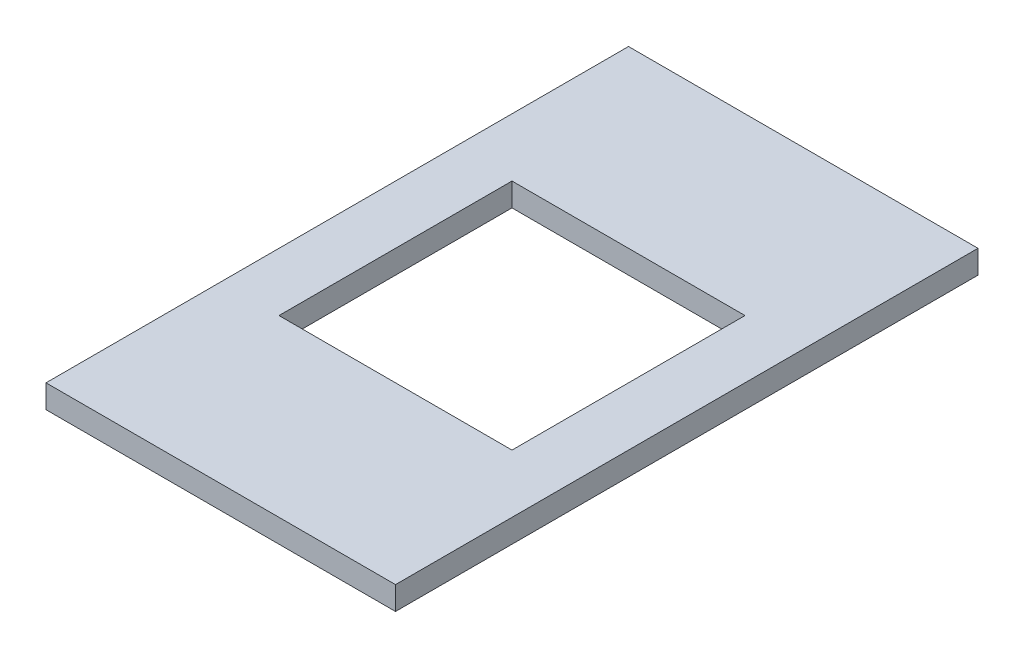
SolidWorks part; units mm, degrees
ref_plane "Front Plane" through (0, 0, 0) normal (0, 0, 1) x (1, 0, 0)
ref_plane "Top Plane" through (0, 0, 0) normal (0, 1, 0) x (1, 0, 0)
ref_plane "Right Plane" through (0, 0, 0) normal (1, 0, 0) x (0, 0, -1)
sketch "Sketch1" plane through (0, 0, 0) normal (0, 1, 0) x (1, 0, 0)
  line L1 (0, 0) -> (-150, 0)
  line L2 (0, 0) -> (0, 30)
  line L3 (0, 30) -> (-150, 30)
  line L4 (-150, 0) -> (-150, 30)
  dimension "D1" = 30
  dimension "D2" = 150
extrude "Boss-Extrude1" add sketch "Sketch1" along normal blind 10
sketch "Sketch8" plane through (0, 0, 0) normal (0, -1, 0) x (-1, 0, 0)
  line L0 (150, 0) -> (0, 30)
  line L1 (150, 30) -> (0, 0)
  line L2 (150, 0) -> (0, 0) construction
sketch "Sketch9" plane through (0, 0, 0) normal (0, -1, 0) x (1, 0, 0)
  line L0 (-150, -30) -> (0, 0) construction
  line L1 (0, -140) -> (-150, -140)
  line L2 (0, -140) -> (0, 110)
  line L3 (0, 110) -> (-150, 110)
  line L4 (-150, -140) -> (-150, 110)
  line L5 (0, -140) -> (-150, 110) construction
  line L6 (0, 110) -> (-150, -140) construction
  line L8 (-125, -65) -> (-25, -65)
  line L9 (-125, -65) -> (-125, 35)
  line L10 (-125, 35) -> (-25, 35)
  line L11 (-25, -65) -> (-25, 35)
  line L12 (-125, -65) -> (-25, 35) construction
  line L13 (-125, 35) -> (-25, -65) construction
  point P0 (-75, -15)
  point P7 (-75, -15)
  point P12 (-75, 110)
  point P13 (-75, -140)
  dimension "D1" = 250
  dimension "D2" = 150
  dimension "D3" = 100
  dimension "D4" = 100
extrude "Boss-Extrude3" add sketch "Sketch9" along normal blind 10
sketch "Sketch19" plane through (0, -10, 0) normal (0, -1, 0) x (1, 0, 0)
  line L0 (-125, 35) -> (-125, 110)
  line L1 (0, 110) -> (-150, 110) construction
  line L2 (-25, 35) -> (-25, 110)
  line L3 (-125, 72.5) -> (-25, 72.5)
  line L4 (-125, -15) -> (-25, -15)
  line L5 (-125, 35) -> (-125, -65) construction
  line L6 (-25, -65) -> (-25, 35) construction
ref_point "Point1"
sketch "Sketch25" plane through (0, 0, 0) normal (0, 1, 0) x (1, 0, 0)
  line L1 (0, 30) -> (-150, 30)
  line L2 (0, 30) -> (0, 0)
  line L3 (0, 0) -> (-150, 0)
  line L4 (-150, 30) -> (-150, 0)
extrude "Cut-Extrude2" cut sketch "Sketch25" along normal blind 10
ref_point "Point2"
ref_point "Point3"
ref_point "Point4"
